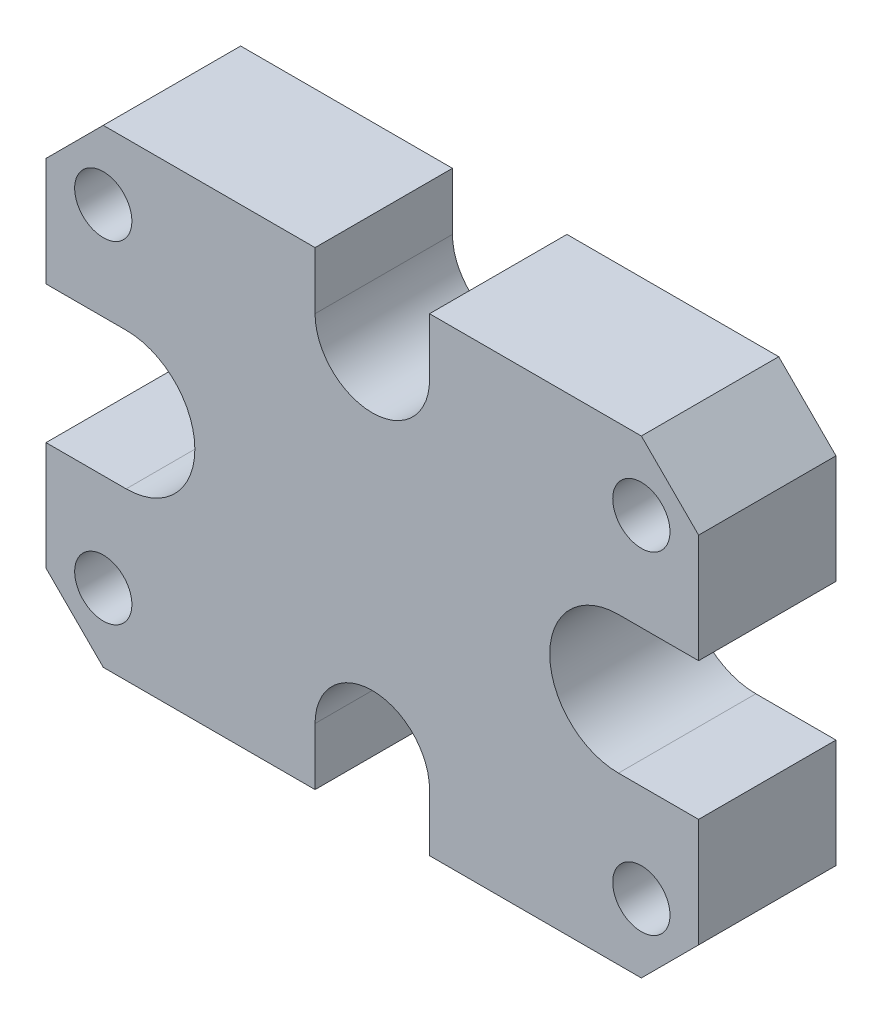
SolidWorks part; units mm, degrees
ref_plane "Front Plane" through (0, 0, 0) normal (0, 0, 1) x (1, 0, 0)
ref_plane "Top Plane" through (0, 0, 0) normal (0, 1, 0) x (1, 0, 0)
ref_plane "Right Plane" through (0, 0, 0) normal (1, 0, 0) x (0, 0, -1)
sketch "Sketch1" plane through (0, 0, 0) normal (0, 0, 1) x (1, 0, 0)
  line L0 (0, 0) -> (0, -34483.4089) construction
  line L1 (0, 0) -> (-34483.4089, 0) construction
  line L2 (-10, 41) -> (-10, 31)
  line L3 (-47, 41) -> (-10, 41)
  line L4 (-57, 31) -> (-57, 12)
  line L5 (-47, -41) -> (-10, -41)
  line L6 (57, 31) -> (57, 12)
  line L7 (-57, 41) -> (-51.1837, 36.8163) construction
  line L8 (-57, -41) -> (-51.1837, -36.8163) construction
  line L9 (10, 31) -> (10, 41)
  line L10 (10, 41) -> (47, 41)
  line L11 (10, -31) -> (10, -41)
  line L12 (-10, -41) -> (-10, -31)
  line L13 (10, -41) -> (47, -41)
  line L14 (57, 12) -> (43, 12)
  line L15 (43, -12) -> (57, -12)
  line L16 (57, -12) -> (57, -31)
  line L17 (-43, -12) -> (-57, -12)
  line L18 (-57, 12) -> (-43, 12)
  line L19 (-57, -12) -> (-57, -31)
  line L20 (-57, 31) -> (-47, 41)
  line L21 (47, 41) -> (57, 31)
  line L22 (-57, -31) -> (-47, -41)
  line L23 (47, -41) -> (57, -31)
  line L24 (51.1837, -36.8163) -> (57, -41) construction
  line L25 (51.1837, 36.8163) -> (57, 41) construction
  arc A0 (-10, 31) -> (10, 31) centre (0, 31) ccw
  arc A1 (-10, -31) -> (10, -31) centre (0, -31) cw
  arc A2 (43, 12) -> (43, -12) centre (43, 0) ccw
  arc A3 (-43, 12) -> (-43, -12) centre (-43, 0) cw
  circle A8 centre (-47, 29) radius 5
  circle A9 centre (47, 29) radius 5
  circle A10 centre (-47, -29) radius 5
  circle A11 centre (47, -29) radius 5
  point P5 (0, 0)
  point P50 (0, 0)
  dimension "D6" = 14
  dimension "D7" = 10
  dimension "D1" = 114
  dimension "D2" = 82
  dimension "D3" = 20
  dimension "D4" = 10
  dimension "D5" = 24
  dimension "D8" = 12
extrude "Boss-Extrude1" add sketch "Sketch1" along normal mid plane 24
